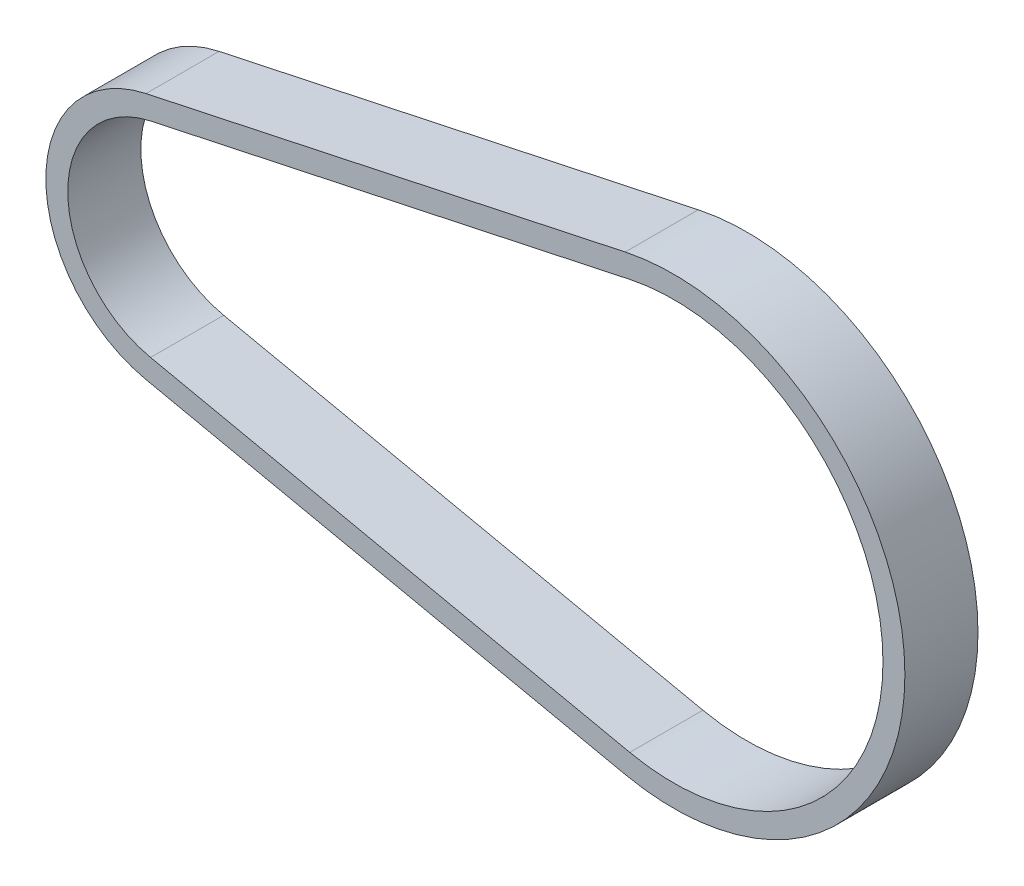
SolidWorks part; units mm, degrees
material "C (Graphite)"
ref_plane "Plan de face" through (0, 0, 0) normal (0, 0, 1) x (1, 0, 0)
ref_plane "Plan de dessus" through (0, 0, 0) normal (0, 1, 0) x (1, 0, 0)
ref_plane "Plan de droite" through (0, 0, 0) normal (1, 0, 0) x (0, 0, -1)
sketch "Sketch1" plane through (0, 0, 0) normal (0, 0, 1) x (1, 0, 0)
  line L0 (-34.275, 0) -> (34.275, 0) construction
  line L1 (-37.2685, 14.0087) -> (28.288, 28.0175)
  line L2 (-37.2685, -14.0087) -> (28.288, -28.0175)
  line L3 (-37.8954, 16.9425) -> (27.6611, 30.9512)
  line L4 (-37.8954, -16.9425) -> (27.6611, -30.9512)
  arc A0 (-37.2685, 14.0087) -> (-37.2685, -14.0087) centre (-34.275, 0) ccw
  arc A1 (28.288, -28.0175) -> (28.288, 28.0175) centre (34.275, 0) ccw
  arc A2 (27.6611, -30.9512) -> (27.6611, 30.9512) centre (34.275, 0) ccw
  arc A3 (-37.8954, 16.9425) -> (-37.8954, -16.9425) centre (-34.275, 0) ccw
  point P3 (0, 0)
  dimension "D2" = 57.3
  dimension "D3" = 28.65
  dimension "D1" = 68.55
  dimension "D4" = 3
extrude "Boss-Extrude1" add sketch "Sketch1" along normal mid plane 10
